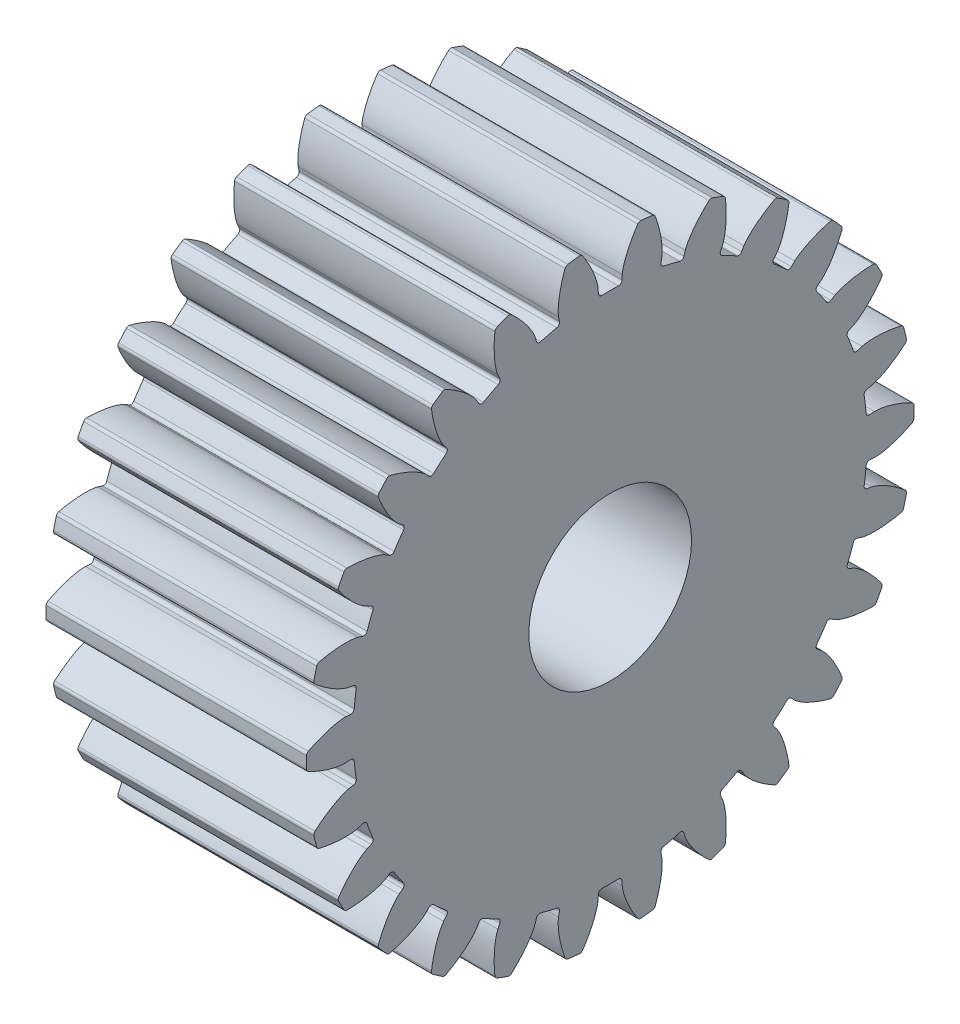
SolidWorks part; units mm, degrees
ref_plane "Front Plane" through (0, 0, 0) normal (1, 0, 0) x (0, 1, 0)
ref_plane "Top Plane" through (0, 0, 0) normal (0, 0, 1) x (0, 1, 0)
ref_plane "Right Plane" through (0, 0, 0) normal (0, 1, 0) x (-1, 0, 0)
sketch "Sketch2" plane through (0, 0, 0) normal (1, 0, 0) x (0, 1, 0)
  circle A0 centre (0, 0) radius 3.9688
  circle A1 centre (0, 0) radius 14.8167
  dimension "D1" = 7.9375
  dimension "D2" = 29.6333
extrude "Gear Width Extrude" add sketch "Sketch2" along normal blind 12.7
sketch "Sketch3" plane through (0, 0, 0) normal (1, 0, 0) x (0, 1, 0)
  line L0 (-14.8167, 0) -> (14.8167, 0) construction
  line L1 (0, 14.8167) -> (0, -14.8167) construction
  line L2 (0, 0) -> (12.9152, 0.5882) construction
  line L5 (12.5338, 0) -> (14.8167, 0)
  line L6 (12.9152, 0.5882) -> (12.5209, 0.5702)
  circle A0 centre (0, 0) radius 12.5338 construction
  circle A1 centre (0, 0) radius 12.9286 construction
  circle A2 centre (0, 0) radius 13.7583 construction
  circle A3 centre (0, 0) radius 14.8167 construction
  arc A7 (14.7499, 1.4052) -> (14.8167, 0) centre (0, 0) cw
  arc A8 (12.5209, 0.5702) -> (12.5338, 0) centre (0, 0) cw
  spline S0 degree 4 poles (12.9152, 0.5882) (12.9182, 0.5884) (12.9266, 0.589) (12.9524, 0.5915) (13.0033, 0.5985) (13.0658, 0.61) (13.1375, 0.6259) (13.2064, 0.6434) (13.2652, 0.6597) (13.3236, 0.6772) (13.3817, 0.6958) (13.4518, 0.7196) (13.5357, 0.7499) (13.6332, 0.788) (13.7433, 0.8343) (13.8548, 0.8849) (13.9641, 0.9373) (14.0738, 0.9935) (14.1795, 1.05) (14.2886, 1.1119) (14.389, 1.1707) (14.5005, 1.2401) (14.5903, 1.2971) (14.7079, 1.376) (14.777, 1.4237) (14.8576, 1.4809) (14.8932, 1.5069) (14.9151, 1.5229) knots 0 0 0 0 0 0.005377 0.015084 0.04661 0.092111 0.119476 0.146842 0.174209 0.201575 0.228941 0.256307 0.307035 0.361767 0.4165 0.471232 0.525964 0.580697 0.635429 0.690161 0.744894 0.799626 0.854358 0.909091 0.954545 1 1 1 1 1 construction
  spline S1 degree 4 poles (12.9152, 0.5882) (12.9182, 0.5884) (12.9266, 0.589) (12.9524, 0.5915) (13.0033, 0.5985) (13.0658, 0.61) (13.1375, 0.6259) (13.2064, 0.6434) (13.2652, 0.6597) (13.3236, 0.6772) (13.3817, 0.6958) (13.4518, 0.7196) (13.5357, 0.7499) (13.6332, 0.788) (13.7433, 0.8343) (13.8548, 0.8849) (13.9641, 0.9373) (14.0738, 0.9935) (14.1795, 1.05) (14.2886, 1.1119) (14.389, 1.1707) (14.5005, 1.2401) (14.5903, 1.2971) (14.6824, 1.3589) (14.7271, 1.3894) (14.7499, 1.4052) knots 0 0 0 0 0 0.005377 0.015084 0.04661 0.092111 0.119476 0.146842 0.174209 0.201575 0.228941 0.256307 0.307035 0.361767 0.4165 0.471232 0.525964 0.580697 0.635429 0.690161 0.744894 0.799626 0.854358 0.909091 0.909091 0.909091 0.909091 0.909091
  dimension "D1" = 27.5167
  dimension "D2" = 25.8572
  dimension "D3" = 25.0677
extrude "Gear Tooth Cut" cut sketch "Sketch3" along normal blind 25.4
mirror "Gear Tooth Cut Mirror" about plane through (25.4, 0, 0) normal (0, 0, 1) of "Gear Tooth Cut"
fillet "Tooth Fillets" radius 0.1662 4 edges at (6.35, 14.7499, 1.4052) (6.35, 14.7499, -1.4052) (6.35, 12.5209, 0.5702) (6.35, 12.5209, -0.5702)
pattern_circular "CirPattern1" count 26 over 360 about axis through (0, 0, 0) along (1, 0, 0) of "Gear Tooth Cut", "Gear Tooth Cut Mirror", "Tooth Fillets"
equation "\"DP\"= 24'INPUT: Diametral Pitch"
equation "\"a_Pressure\"= 20'INPUT: Pressure Angle"
equation "\"Z\" = 26'INPUT: Number of Teeth"
equation "\"w_Face\"= 0.5'INPUT: Face Width"
equation "\"d_Bore\"= 5 / 16'INPUT: Bore Diameter"
equation "\"d_Pitch\"= \"Z\" / \"DP\"'Pitch Diameter"
equation "\"Module\"= 1 / \"DP\"'Module"
equation "\"d_Base\"= \"d_Pitch\" * cos ( \"a_Pressure\" )'Base Circle Diameter"
equation "\"Clearance\"= 0.157 / \"DP\"'Clearance"
equation "\"CP\"= pi * \"d_Pitch\" / \"Z\"'Circular Pitch"
equation "\"h_Addendum\"= 1 / \"DP\"'Addendum Depth"
equation "\"h_Dedendum\"= IIF ( \"h_deStandard\" > \"h_deMin\" , \"h_deStandard\" , \"h_deMin\" )'Dedendum Depth"
equation "\"d_Addendum\"= \"d_Pitch\" + ( 2 * \"h_Addendum\" )'Addendum (Tip) Diameter"
equation "\"d_Dedendum\"= \"d_Pitch\" - ( 2 * \"h_Dedendum\" )'Dedendum (Root) Diameter"
equation "\"a_Pitch\"= 360 / \"Z\"'Pitch Angle"
equation "\"a_Alpha\"= ( ( 180 * ( ( \"d_Pitch\" ^ 2 ) - ( \"d_Base\" ^ 2 ) ) ^ 0.5 ) / ( pi * \"d_Base\" ) ) - \"a_Pressure\"'Alpha Angle"
equation "\"a_Beta\"= ( \"a_Pitch\" / 4 ) - \"a_Alpha\"'Beta Angle"
equation "\"ICDP\"= ( ( ( \"d_Addendum\" / 2 ) ^ 2 - ( \"d_Base\" / 2 ) ^ 2 ) ^ 0.5 ) * ( 2 / \"d_Base\" )'Involute Curve Domain Parameter"
equation "\"D1@Sketch2\"=\"d_Bore\""
equation "\"D2@Sketch2\"=\"d_Addendum\""
equation "\"D1@Gear Width Extrude\" = \"w_Face\""
equation "\"D1@Sketch3\"=\"d_Pitch\""
equation "\"D2@Sketch3\"=\"d_Base\""
equation "\"D3@Sketch3\"= \"d_Dedendum\""
equation "\"D1@CirPattern1\"=\"Z\""
equation "\"D1@Tooth Fillets\"=\"Clearance\""
equation "\"h_deStandard\"= ( 1 / \"DP\" ) + \"Clearance\""
equation "\"h_deMin\"= ( \"d_Pitch\" * ( 1 - cos ( \"a_Pressure\" ) ) / 2 ) + \"Clearance\""
